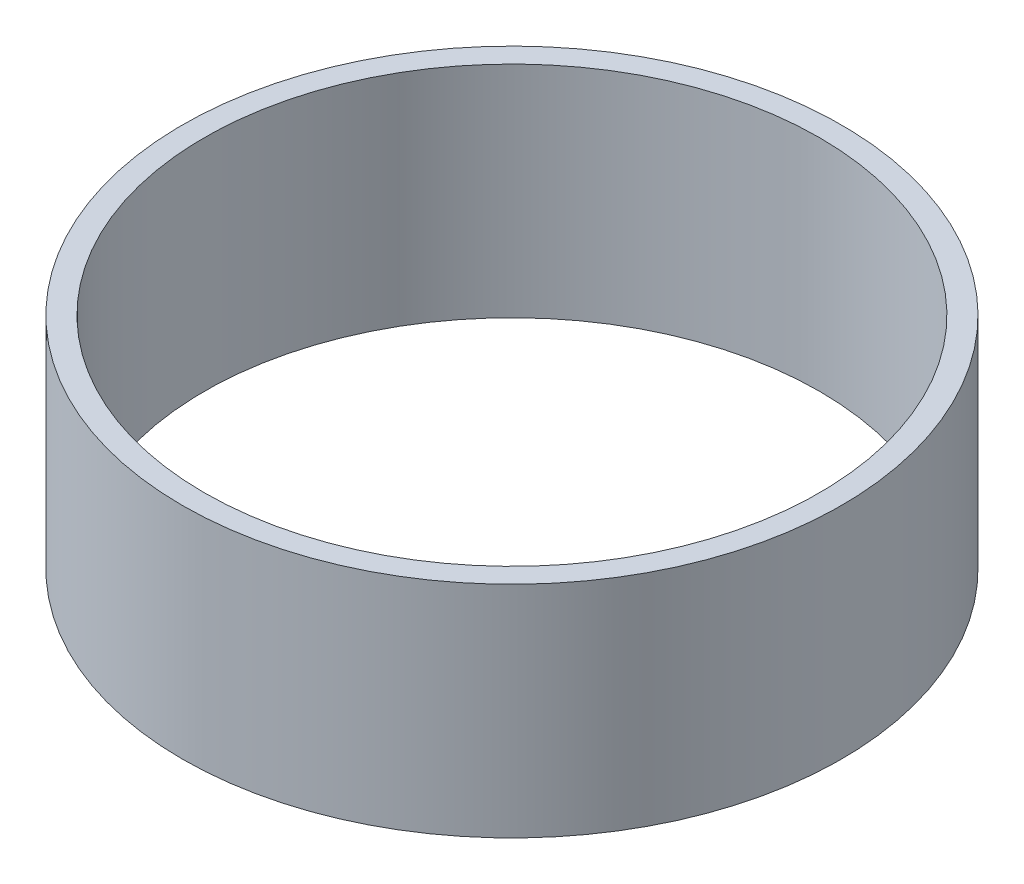
SolidWorks part; units mm, degrees
material "聚亚安酯(11671)"
ref_plane "前视基准面" through (0, 0, 0) normal (0, 0, 1) x (1, 0, 0)
ref_plane "上视基准面" through (0, 0, 0) normal (0, 1, 0) x (1, 0, 0)
ref_plane "右视基准面" through (0, 0, 0) normal (1, 0, 0) x (0, 0, -1)
sketch "草图1" plane through (0, 0, 0) normal (0, 1, 0) x (1, 0, 0)
  circle A0 centre (0, 0) radius 75
  circle A1 centre (0, 0) radius 70
  dimension "D1" = 140
  dimension "D2" = 150
extrude "凸台-拉伸1" add sketch "草图1" along normal mid plane 50
move or copy body "实体-移动/复制1" [suppressed] bodies to move or copy 106
